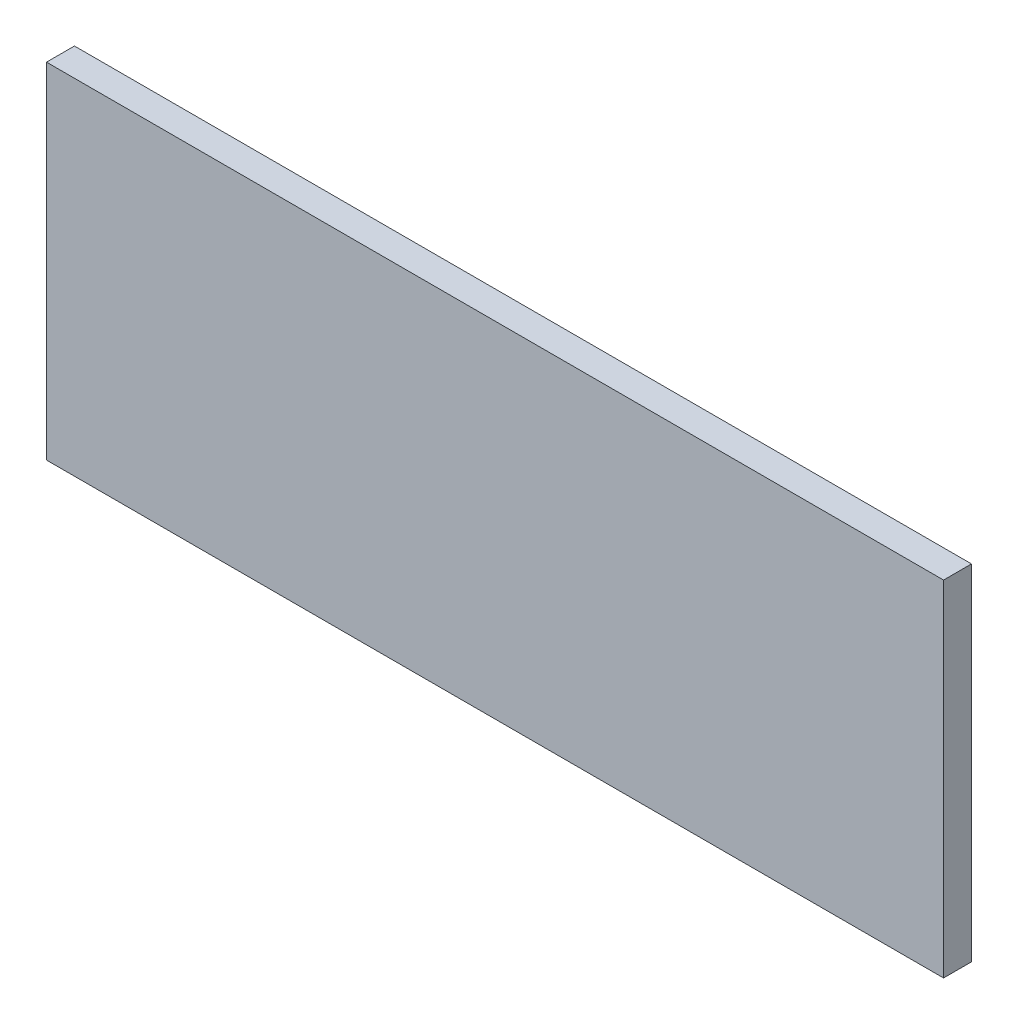
SolidWorks part; units mm, degrees
ref_plane "Front Plane" through (0, 0, 0) normal (0, 0, 1) x (1, 0, 0)
ref_plane "Top Plane" through (0, 0, 0) normal (0, 1, 0) x (1, 0, 0)
ref_plane "Right Plane" through (0, 0, 0) normal (1, 0, 0) x (0, 0, -1)
sketch "Sketch1" plane through (0, 0, 0) normal (0, 0, 1) x (1, 0, 0)
  line L1 (-24.845, 6.9986) -> (39.367, 6.9986)
  line L2 (-24.845, 6.9986) -> (-24.845, 31.6686)
  line L3 (-24.845, 31.6686) -> (39.367, 31.6686)
  line L4 (39.367, 6.9986) -> (39.367, 31.6686)
extrude "Boss-Extrude1" add sketch "Sketch1" along normal blind 2
